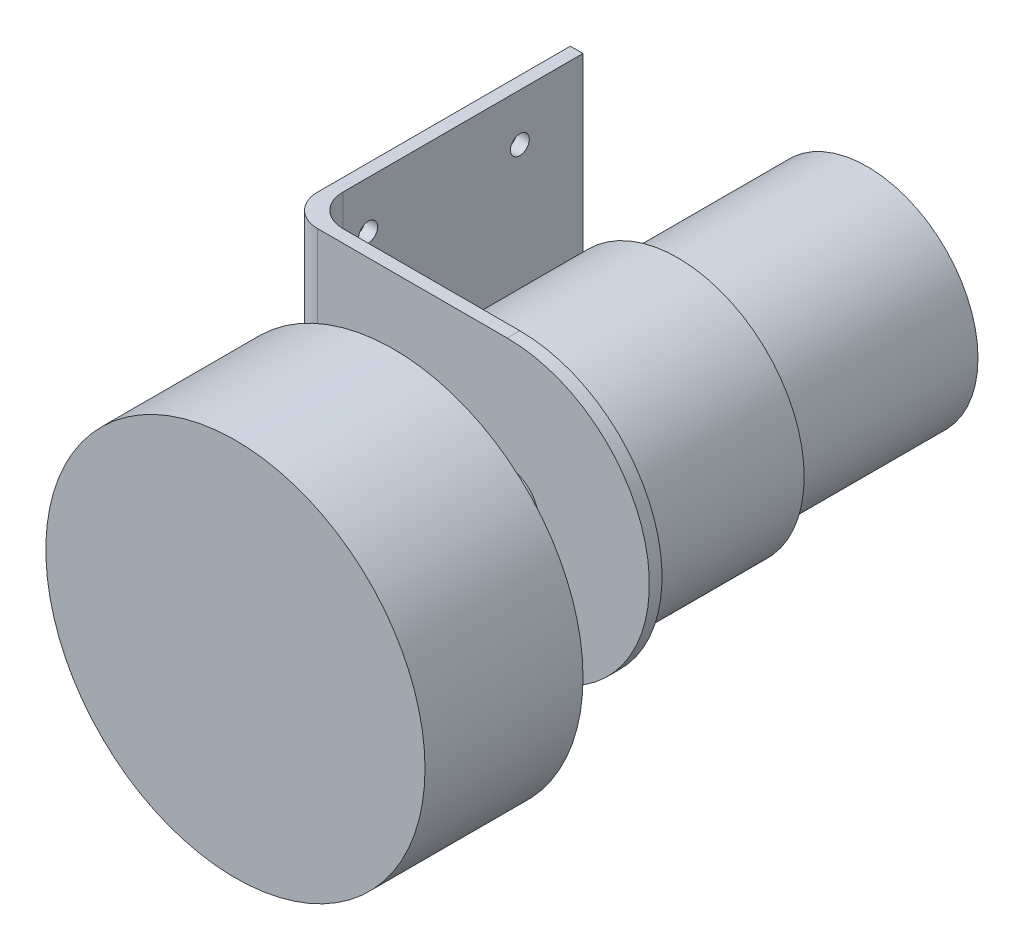
SolidWorks part; units mm, degrees
ref_plane "前视基准面" through (0, 0, 0) normal (0, 0, 1) x (1, 0, 0)
ref_plane "上视基准面" through (0, 0, 0) normal (0, 1, 0) x (1, 0, 0)
ref_plane "右视基准面" through (0, 0, 0) normal (1, 0, 0) x (0, 0, -1)
sketch "草图1" plane through (0, 0, 0) normal (0, 0, 1) x (1, 0, 0)
  circle A0 centre (0, 0) radius 17.5
  dimension "D1" = 35
extrude "凸台-拉伸1" add sketch "草图1" along normal blind 30
sketch "草图2" plane through (0, 0, 30) normal (0, 0, 1) x (1, 0, 0)
  circle A0 centre (0, 0) radius 20
  dimension "D1" = 40
extrude "凸台-拉伸2" add sketch "草图2" along normal blind 25
sketch "草图3" plane through (0, 0, 0) normal (0, 0, -1) x (-1, 0, 0)
  circle A0 centre (0, 0) radius 5
  dimension "D1" = 10
extrude "凸台-拉伸3" add sketch "草图3" against normal blind 100
sketch "草图4" plane through (0, 0, 100) normal (0, 0, 1) x (1, 0, 0)
  circle A0 centre (0, 0) radius 30
  dimension "D1" = 60
extrude "凸台-拉伸4" add sketch "草图4" against normal blind 25
sketch "草图6" plane through (0, 0, 55) normal (0, 0, 1) x (1, 0, 0)
  line L0 (0, 22.5) -> (-35, 22.5)
  line L1 (-35, 22.5) -> (-35, -22.5)
  line L2 (-35, -22.5) -> (0, -22.5)
  arc A0 (0, -22.5) -> (0, 22.5) centre (0, 0) ccw
  dimension "D1" = 45
  dimension "D2" = 35
extrude "凸台-拉伸5" add sketch "草图6" along normal blind 2
sketch "草图7" plane through (0, 0, 57) normal (0, 0, 1) x (1, 0, 0)
  line L0 (-35, 22.5) -> (-33, 22.5)
  line L1 (0, 22.5) -> (-35, 22.5) construction
  line L2 (-33, 22.5) -> (-33, -22.5)
  line L3 (-35, -22.5) -> (0, -22.5) construction
  line L4 (-33, -22.5) -> (-35, -22.5)
  line L5 (-35, -22.5) -> (-35, 22.5)
  dimension "D1" = 2
extrude "凸台-拉伸6" add sketch "草图7" against normal blind 45
fillet "圆角3" radius 5 2 edges at (-33, 0, 55) (-35, 0, 57)
sketch "草图8" plane through (-35, 0, 0) normal (-1, 0, 0) x (0, 0, 1)
  line L0 (26.8962, 0) -> (47.9887, 0) construction
  line L1 (12, 22.5) -> (12, -22.5) construction
  circle A0 centre (22, 15) radius 1.5
  circle A1 centre (22, -15) radius 1.5
  circle A2 centre (46, 15) radius 1.5
  circle A3 centre (46, -15) radius 1.5
  dimension "D1" = 3
  dimension "D2" = 30
  dimension "D3" = 3
  dimension "D4" = 24
  dimension "D5" = 10
extrude "切除-拉伸1" cut sketch "草图8" against normal blind 5
